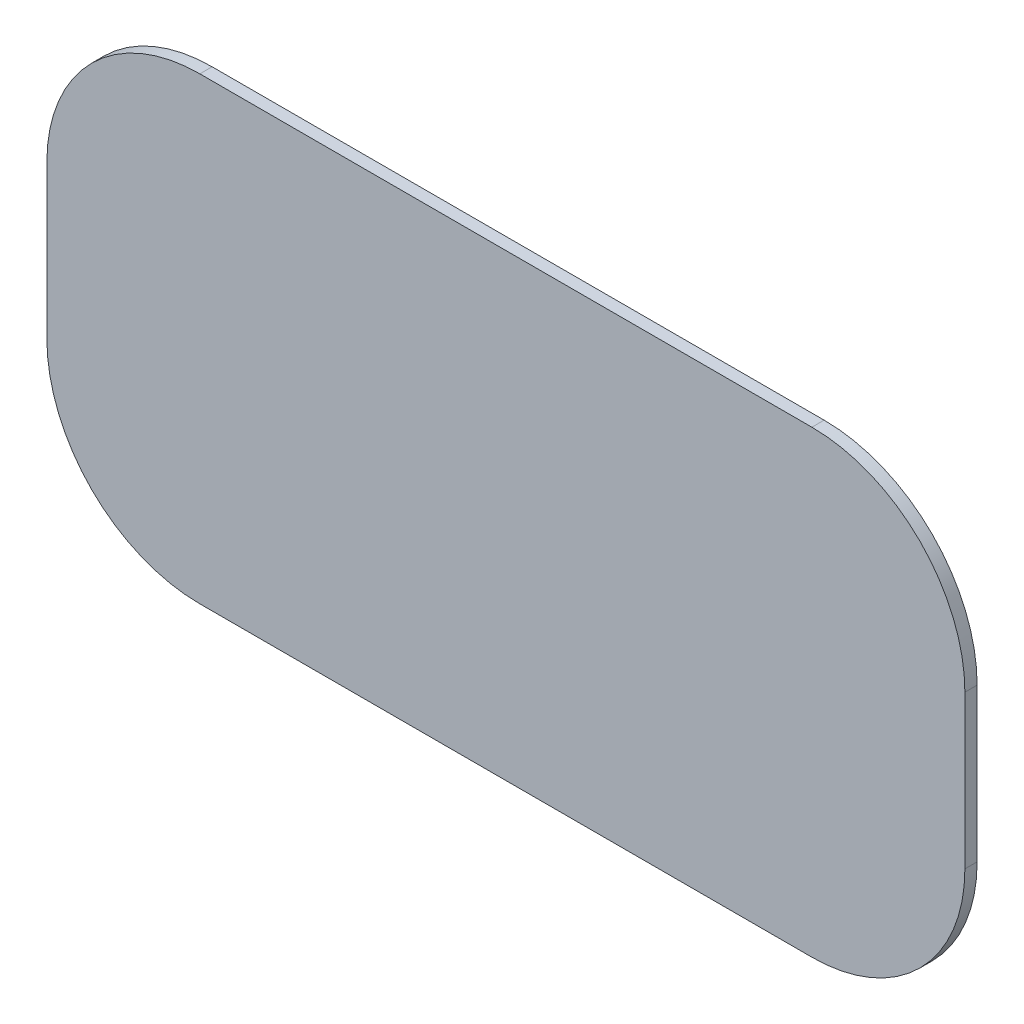
SolidWorks part; units mm, degrees
ref_plane "Ebene vorne" through (0, 0, 0) normal (0, 0, 1) x (1, 0, 0)
ref_plane "Ebene oben" through (0, 0, 0) normal (0, 1, 0) x (1, 0, 0)
ref_plane "Ebene rechts" through (0, 0, 0) normal (1, 0, 0) x (0, 0, -1)
sketch "Skizze1" plane through (0, 0, 0) normal (0, 0, 1) x (1, 0, 0)
  line L0 (10, 0) -> (50, 0)
  line L1 (10, 0) -> (50, 0) construction
  line L2 (0, -10) -> (0, -20) construction
  line L3 (10, -30) -> (50, -30) construction
  line L4 (60, -10) -> (60, -20) construction
  line L5 (60, -10) -> (60, -20)
  line L6 (10, -30) -> (50, -30)
  line L7 (0, -10) -> (0, -20)
  arc A0 (0, -20) -> (10, -30) centre (10, -20) ccw construction
  arc A1 (50, -30) -> (60, -20) centre (50, -20) ccw construction
  arc A2 (50, 0) -> (60, -10) centre (50, -10) cw construction
  arc A3 (10, 0) -> (0, -10) centre (10, -10) ccw construction
  arc A4 (50, 0) -> (60, -10) centre (50, -10) cw
  arc A5 (50, -30) -> (60, -20) centre (50, -20) ccw
  arc A6 (0, -20) -> (10, -30) centre (10, -20) ccw
  arc A7 (10, 0) -> (0, -10) centre (10, -10) ccw
  point P7 (0, -30)
  point P10 (60, -30)
  point P13 (60, 0)
  point P16 (0, 0)
  dimension "D3" = 10
  dimension "D1" = 60
  dimension "D2" = 30
  dimension "D4" = 0
extrude "Aufsatz-Linear austragen1" add sketch "Skizze1" along normal blind 0.8
